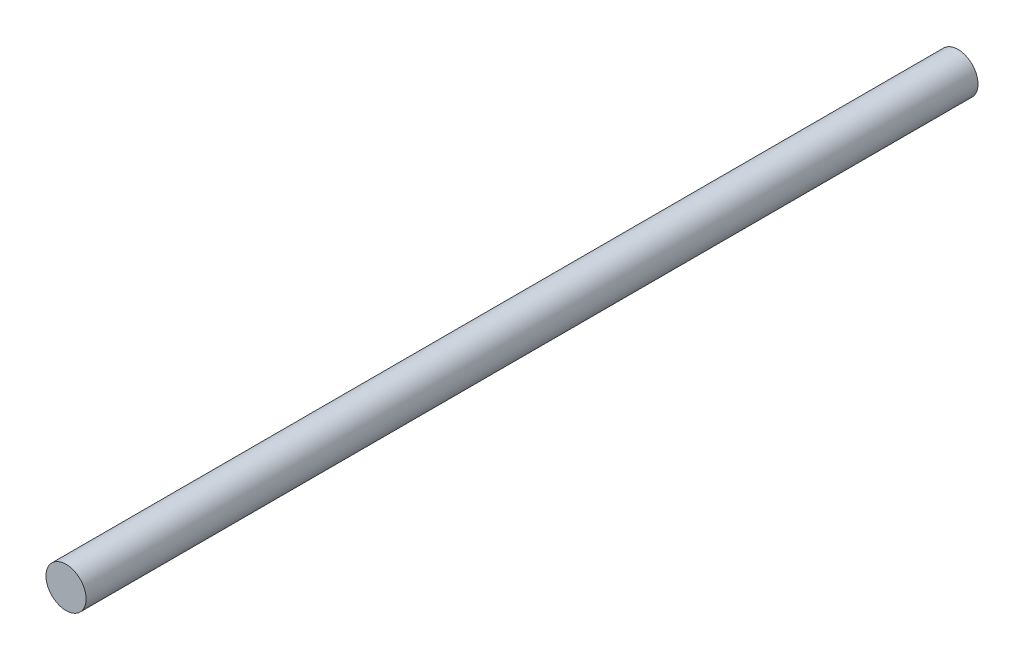
SolidWorks part; units mm, degrees
ref_plane "Plano frontal" through (0, 0, 0) normal (0, 0, 1) x (1, 0, 0)
ref_plane "Plano superior" through (0, 0, 0) normal (0, 1, 0) x (1, 0, 0)
ref_plane "Plano direito" through (0, 0, 0) normal (1, 0, 0) x (0, 0, -1)
sketch "Esboço1" plane through (0, 0, 0) normal (0, 0, 1) x (1, 0, 0)
  circle A0 centre (0, 0) radius 4.2
  dimension "D1" = 8.4
extrude "Ressalto-extrusão1" add sketch "Esboço1" along normal blind 186.6
